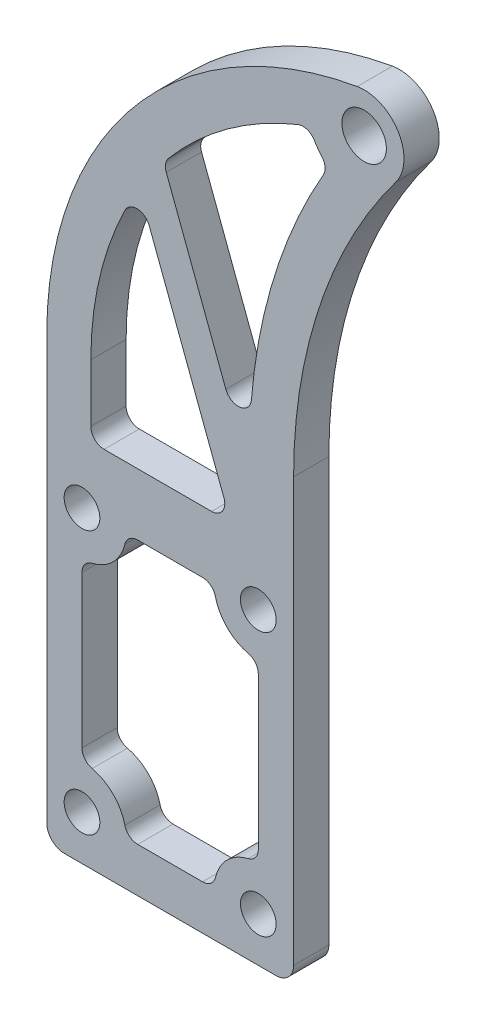
SolidWorks part; units mm, degrees
material "Thornel Mat VMA"
ref_plane "前视基准面" through (0, 0, 0) normal (0, 0, 1) x (1, 0, 0)
ref_plane "上视基准面" through (0, 0, 0) normal (0, 1, 0) x (1, 0, 0)
ref_plane "右视基准面" through (0, 0, 0) normal (1, 0, 0) x (0, 0, -1)
other "Configuration Table"
sketch "草图1" plane through (0, 0, 0) normal (0, 0, 1) x (1, 0, 0)
  line L1 (-14, -25) -> (14, -25)
  line L2 (-14, -25) -> (-14, 25)
  line L4 (14, -25) -> (14, 25)
  line L5 (-14, -25) -> (14, 25) construction
  line L6 (-14, 25) -> (14, -25) construction
  circle A0 centre (22, 62.5) radius 1.525
  arc A1 (25.6167, 59.7807) -> (21.2155, 66.9565) centre (22, 62.5) ccw
  arc A2 (-14, 25) -> (21.2155, 66.9565) centre (28.6017, 25) cw
  arc A3 (14, 25) -> (25.6167, 59.7807) centre (71.8752, 25) cw
  point P0 (0, 0)
  dimension "D5" = 3.05
  dimension "D6" = 3
  dimension "D1" = 28
  dimension "D2" = 50
  dimension "D3" = 8
  dimension "D4" = 28
  dimension "D7" = 50
  dimension "D8" = 37.5
extrude "凸台-拉伸1" add sketch "草图1" along normal mid plane 4
fillet "圆角1" radius 2 2 edges at (-14, -25, 0) (14, -25, 0)
sketch "草图3" plane through (0, 0, 2) normal (0, 0, 1) x (1, 0, 0)
  circle A0 centre (22, 62.5) radius 2.525
  dimension "D1" = 5.05
extrude "切除-拉伸1" cut sketch "草图3" against normal mid plane 22
sketch "草图4" plane through (0, 0, 2) normal (0, 0, 1) x (1, 0, 0)
  circle A0 centre (-10.0046, 9.95) radius 1.65 construction
  circle A1 centre (9.9954, 9.95) radius 1.65 construction
  circle A2 centre (9.9954, -19.95) radius 1.65 construction
  circle A3 centre (-10.0046, -19.95) radius 1.65 construction
  circle A4 centre (-10.0046, 9.95) radius 1.65 construction
  circle A5 centre (9.9954, 9.95) radius 1.65 construction
  circle A6 centre (9.9954, -19.95) radius 1.65 construction
  circle A7 centre (-10.0046, -19.95) radius 1.65 construction
  circle A8 centre (-10.0046, 9.95) radius 2.025
  circle A9 centre (9.9954, 9.95) radius 2.025
  circle A10 centre (9.9954, -19.95) radius 2.025
  circle A11 centre (-10.0046, -19.95) radius 2.025
  dimension "D1" = 4.05
extrude "切除-拉伸2" cut sketch "草图4" against normal blind 20
sketch "草图5" plane through (0, 0, 2) normal (0, 0, 1) x (1, 0, 0)
  line L1 (-10.0046, -19.95) -> (9.9954, -19.95)
  line L2 (-10.0046, -19.95) -> (-10.0046, 9.95)
  line L3 (-10.0046, 9.95) -> (9.9954, 9.95)
  line L4 (9.9954, -19.95) -> (9.9954, 9.95)
  line L5 (-10.0046, -19.95) -> (9.9954, 9.95) construction
  line L6 (-10.0046, 9.95) -> (9.9954, -19.95) construction
  circle A0 centre (9.9954, 9.95) radius 5
  circle A1 centre (-10.0046, 9.95) radius 5
  circle A2 centre (-10.0046, -19.95) radius 5
  circle A3 centre (9.9954, -19.95) radius 5
  point P12 (-0.0046, -5)
  dimension "D1" = 10
extrude "切除-拉伸3" cut sketch "草图5" against normal blind 20 contours A3 L4 A0 L3 A1 L2 A2 L1
fillet "圆角2" radius 1.5 8 edges at (-5.0046, -19.95, 0) (-10.0046, -14.95, 0) (4.9954, 9.95, 0) (9.9954, 4.95, 0) (9.9954, -14.95, 0) (4.9954, -19.95, 0) (-5.0046, 9.95, 0) (-10.0046, 4.95, 0)
sketch "草图6" plane through (0, 0, 2) normal (0, 0, 1) x (1, 0, 0)
  line L0 (-9, 25) -> (-9, 16.95)
  line L1 (-9, 16.95) -> (9, 16.95)
  line L2 (9, 16.95) -> (9, 25)
  arc A2 (25.6167, 59.7807) -> (14, 25) centre (71.8752, 25) ccw construction
  arc A3 (21.2155, 66.9565) -> (-14, 25) centre (28.6017, 25) ccw construction
  circle A5 centre (-10.0046, 9.95) radius 2.025 construction
  arc A8 (15.8333, 60.3674) -> (17.9712, 57.3674) centre (22, 62.5) ccw
  circle A9 centre (22, 62.5) radius 2.525 construction
  arc A10 (17.9712, 57.3674) -> (9, 25) centre (71.8752, 25) ccw
  arc A11 (15.8333, 60.3674) -> (-9, 25) centre (28.6017, 25) ccw
  dimension "D4" = 4
  dimension "D1" = 5
  dimension "D2" = 5
  dimension "D3" = 7
extrude "切除-拉伸4" cut sketch "草图6" against normal blind 10
sketch "草图7" plane through (0, 0, 2) normal (0, 0, 1) x (1, 0, 0)
  line L0 (-2.1717, 46.6076) -> (9, 16.95) construction
  line L1 (-4.0433, 45.9026) -> (7.1284, 16.245)
  line L2 (-0.7488, 48.5039) -> (10.8716, 17.655)
  line L3 (-0.3, 47.3126) -> (10.8716, 17.655) construction
  line L4 (7.1284, 16.245) -> (10.8716, 17.655)
  line L5 (-0.7488, 48.5039) -> (-4.0433, 45.9026)
  arc A0 (15.8333, 60.3674) -> (-9, 25) centre (28.6017, 25) ccw construction
  dimension "D1" = 2
  dimension "D2" = 2
extrude "凸台-拉伸2" add sketch "草图7" against normal up to surface (4 mm away) up to face at (4.2998, 34.3358, -2)
fillet "圆角3" radius 1.5 7 edges at (-0.7488, 48.5039, 0) (15.8333, 60.3674, 0) (9, 22.6236, 0) (17.9712, 57.3674, 0) (-3.5278, 44.5341, 0) (-9, 16.95, 0) (6.8628, 16.95, 0)
